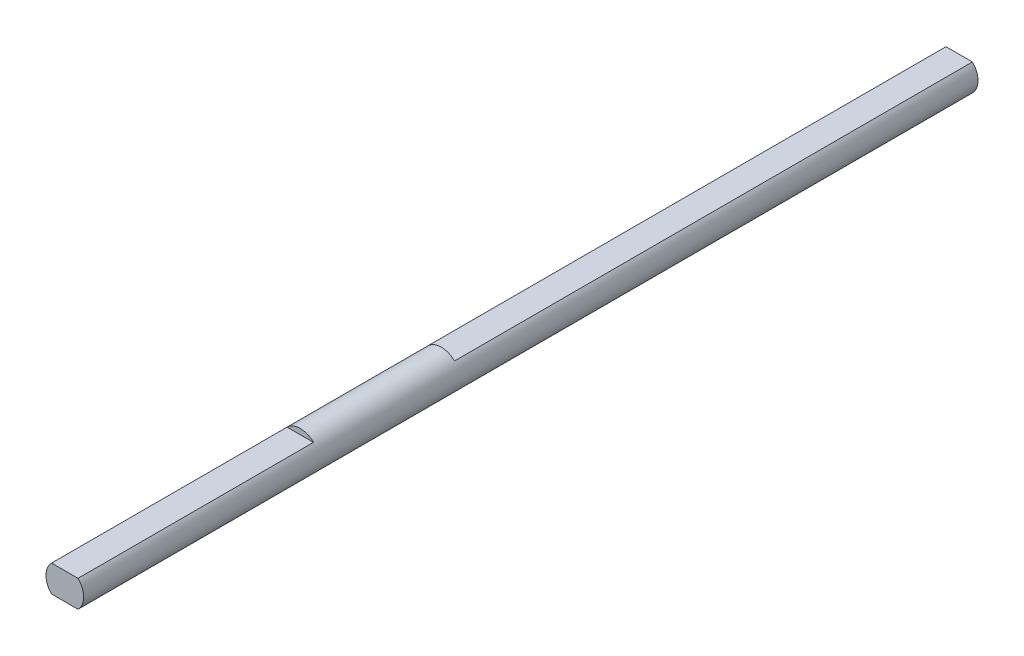
SolidWorks part; units mm, degrees
ref_plane "Plano frontal" through (0, 0, 0) normal (0, 0, 1) x (1, 0, 0)
ref_plane "Plano superior" through (0, 0, 0) normal (0, 1, 0) x (1, 0, 0)
ref_plane "Plano direito" through (0, 0, 0) normal (1, 0, 0) x (0, 0, -1)
sketch "Esboço1" plane through (0, 0, 0) normal (0, 0, 1) x (1, 0, 0)
  circle A0 centre (0, 0) radius 2
extrude "Ressalto-extrusão1" add sketch "Esboço1" along normal blind 65 and the other way blind 30
sketch "Esboço5" plane through (0, 0, 65) normal (0, 0, 1) x (1, 0, 0)
  line L1 (0, 1.425) -> (2.6915, 1.425)
  line L2 (2.6915, 1.425) -> (2.6915, 2.7544)
  line L3 (2.6915, 2.7544) -> (-3.6726, 2.7544)
  line L4 (-3.6726, 2.7544) -> (-3.6726, 1.425)
  line L5 (-3.6726, 1.425) -> (0, 1.425)
  line L6 (0, -1.425) -> (2.6915, -1.425)
  line L7 (2.6915, -1.425) -> (2.6915, -2.855)
  line L8 (2.6915, -2.855) -> (-3.6726, -2.855)
  line L9 (-3.6726, -2.855) -> (-3.6726, -1.425)
  line L10 (-3.6726, -1.425) -> (0, -1.425)
  point P5 (0, 0)
extrude "Corte-extrusão4" cut sketch "Esboço5" against normal blind 25.015
sketch "Esboço6" plane through (0, 0, -30) normal (0, 0, -1) x (-1, 0, 0)
  line L0 (0, 1.425) -> (0, -1.425) construction
  line L1 (0, 1.425) -> (2.6412, 1.425)
  line L2 (2.6412, 1.425) -> (2.6412, 2.5888)
  line L3 (2.6412, 2.5888) -> (-2.8718, 2.5888)
  line L4 (-2.8718, 2.5888) -> (-2.8718, 1.425)
  line L5 (-2.8718, 1.425) -> (0, 1.425)
  line L6 (0, -1.425) -> (2.6412, -1.425)
  line L7 (2.6412, -1.425) -> (2.6412, -2.6936)
  line L8 (2.6412, -2.6936) -> (-2.8718, -2.6936)
  line L9 (-2.8718, -2.6936) -> (-2.8718, -1.425)
  line L10 (-2.8718, -1.425) -> (0, -1.425)
  point P5 (0, 0)
extrude "Corte-extrusão5" cut sketch "Esboço6" against normal blind 55.015
